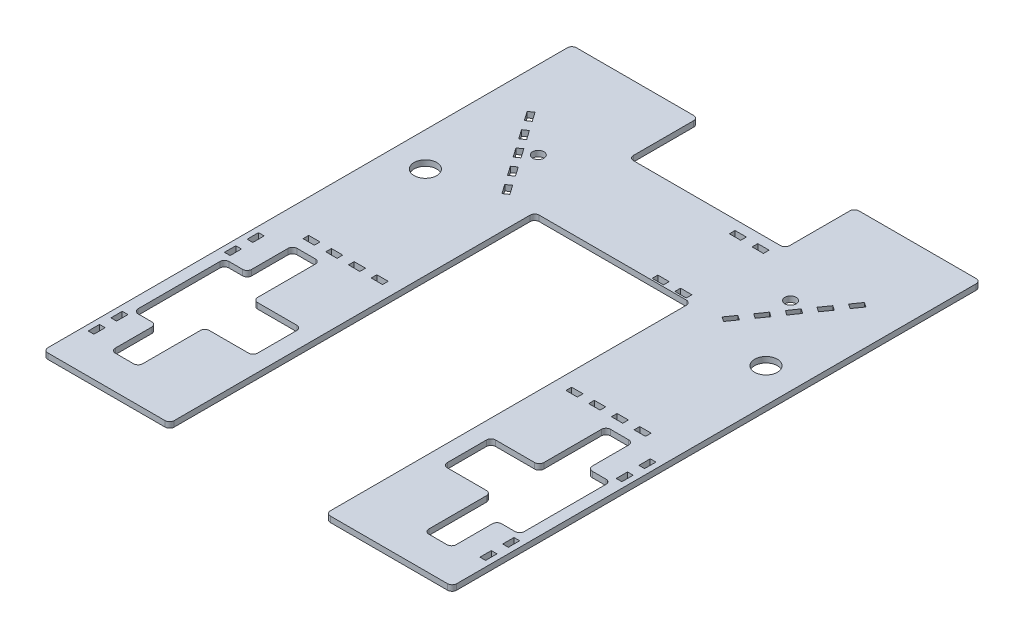
SolidWorks part; units mm, degrees
material "Acrylic (Medium-high impact)"
ref_plane "Front Plane" through (0, 0, 0) normal (0, 0, 1) x (1, 0, 0)
ref_plane "Top Plane" through (0, 0, 0) normal (0, 1, 0) x (1, 0, 0)
ref_plane "Right Plane" through (0, 0, 0) normal (1, 0, 0) x (0, 0, -1)
sketch "Sketch1" plane through (0, 0, 0) normal (0, 1, 0) x (1, 0, 0)
  line L0 (0, 0) -> (0, 279.4)
  line L1 (0, 0) -> (70.625, 0) construction
  line L2 (228.6, 0) -> (228.6, 279.4)
  line L3 (228.6, 279.4) -> (157.975, 178.425) construction
  line L4 (157.975, 178.425) -> (157.975, 0)
  line L5 (194.31, 66.84) -> (167.3225, 66.84)
  line L6 (70.625, 0) -> (70.625, 178.425)
  line L7 (70.625, 178.425) -> (0, 279.4) construction
  line L8 (70.625, 178.425) -> (0, 178.425) construction
  line L9 (157.975, 178.425) -> (228.6, 178.425) construction
  line L10 (0, 279.4) -> (70.625, 279.4)
  line L11 (114.3, -1000) -> (114.3, 49000) construction
  line L12 (194.31, 2.54) -> (209.55, 2.54)
  line L13 (194.31, 2.54) -> (194.31, 39.84)
  line L14 (194.31, 104.14) -> (209.55, 104.14)
  line L15 (222.25, 27.94) -> (222.25, 78.74)
  line L16 (167.3225, 66.84) -> (167.3225, 39.84)
  line L17 (167.3225, 39.84) -> (194.31, 39.84)
  line L18 (194.31, 66.84) -> (194.31, 104.14)
  line L19 (19.05, 78.74) -> (6.35, 78.74)
  line L20 (70.625, 279.4) -> (70.625, 240.6391)
  line L21 (70.625, 240.6391) -> (157.975, 240.6391)
  line L22 (157.975, 240.6391) -> (157.975, 279.4)
  line L23 (157.975, 279.4) -> (228.6, 279.4)
  line L24 (70.625, 178.425) -> (157.975, 178.425) construction
  line L25 (19.05, 27.94) -> (6.35, 27.94)
  line L26 (157.975, 0) -> (228.6, 0) construction
  line L27 (39.37, 53.34) -> (6.35, 53.34) construction
  line L28 (6.35, 27.94) -> (6.35, 78.74)
  line L29 (6.35, 81.915) -> (3.175, 81.915)
  line L30 (6.35, 81.915) -> (6.35, 88.265)
  line L31 (6.35, 88.265) -> (3.175, 88.265)
  line L32 (3.175, 81.915) -> (3.175, 88.265)
  line L33 (6.35, 94.615) -> (3.175, 94.615)
  line L34 (6.35, 94.615) -> (6.35, 100.965)
  line L35 (6.35, 100.965) -> (3.175, 100.965)
  line L36 (3.175, 12.065) -> (3.175, 5.715)
  line L37 (6.35, 5.715) -> (3.175, 5.715)
  line L38 (6.35, 12.065) -> (6.35, 5.715)
  line L39 (6.35, 12.065) -> (3.175, 12.065)
  line L40 (3.175, 24.765) -> (3.175, 18.415)
  line L41 (6.35, 18.415) -> (3.175, 18.415)
  line L42 (6.35, 24.765) -> (6.35, 18.415)
  line L43 (6.35, 24.765) -> (3.175, 24.765)
  line L44 (3.175, 94.615) -> (3.175, 100.965)
  line L45 (19.05, 104.14) -> (19.05, 78.74)
  line L46 (19.05, 2.54) -> (19.05, 27.94)
  line L47 (34.29, 104.14) -> (19.05, 104.14)
  line L48 (34.29, 2.54) -> (34.29, 39.84)
  line L49 (34.29, 2.54) -> (19.05, 2.54)
  line L50 (61.2775, 39.84) -> (34.29, 39.84)
  line L51 (61.2775, 66.84) -> (61.2775, 39.84)
  line L52 (34.29, 66.84) -> (61.2775, 66.84)
  line L53 (34.29, 66.84) -> (34.29, 104.14)
  line L54 (43.955, 113.665) -> (50.305, 113.665)
  line L55 (56.655, 110.49) -> (63.005, 110.49)
  line L56 (56.655, 110.49) -> (56.655, 113.665)
  line L57 (56.655, 113.665) -> (63.005, 113.665)
  line L58 (63.005, 110.49) -> (63.005, 113.665)
  line L59 (43.955, 110.49) -> (43.955, 113.665)
  line L60 (43.955, 110.49) -> (50.305, 110.49)
  line L61 (50.305, 110.49) -> (50.305, 113.665)
  line L62 (31.255, 113.665) -> (37.605, 113.665)
  line L63 (31.255, 110.49) -> (31.255, 113.665)
  line L64 (31.255, 110.49) -> (37.605, 110.49)
  line L65 (37.605, 110.49) -> (37.605, 113.665)
  line L66 (18.555, 113.665) -> (24.905, 113.665)
  line L67 (18.555, 110.49) -> (18.555, 113.665)
  line L68 (18.555, 110.49) -> (24.905, 110.49)
  line L69 (24.905, 110.49) -> (24.905, 113.665)
  line L70 (135.3875, 235.2498) -> (141.7375, 235.2498)
  line L71 (135.3875, 192.0748) -> (141.7375, 192.0748)
  line L72 (135.3875, 192.0748) -> (135.3875, 188.8998)
  line L73 (135.3875, 188.8998) -> (141.7375, 188.8998)
  line L74 (141.7375, 192.0748) -> (141.7375, 188.8998)
  line L75 (148.0875, 192.0748) -> (154.4375, 192.0748)
  line L76 (148.0875, 192.0748) -> (148.0875, 188.8998)
  line L77 (148.0875, 188.8998) -> (154.4375, 188.8998)
  line L78 (203.695, 110.49) -> (203.695, 113.665)
  line L79 (210.045, 110.49) -> (203.695, 110.49)
  line L80 (210.045, 110.49) -> (210.045, 113.665)
  line L81 (210.045, 113.665) -> (203.695, 113.665)
  line L82 (190.995, 110.49) -> (190.995, 113.665)
  line L83 (197.345, 110.49) -> (190.995, 110.49)
  line L84 (197.345, 110.49) -> (197.345, 113.665)
  line L85 (197.345, 113.665) -> (190.995, 113.665)
  line L86 (178.295, 110.49) -> (178.295, 113.665)
  line L87 (184.645, 110.49) -> (178.295, 110.49)
  line L88 (184.645, 110.49) -> (184.645, 113.665)
  line L89 (165.595, 110.49) -> (165.595, 113.665)
  line L90 (171.945, 113.665) -> (165.595, 113.665)
  line L91 (171.945, 110.49) -> (171.945, 113.665)
  line L92 (171.945, 110.49) -> (165.595, 110.49)
  line L93 (184.645, 113.665) -> (178.295, 113.665)
  line L94 (154.4375, 192.0748) -> (154.4375, 188.8998)
  line L95 (135.3875, 235.2498) -> (135.3875, 232.0748)
  line L96 (135.3875, 232.0748) -> (141.7375, 232.0748)
  line L97 (141.7375, 235.2498) -> (141.7375, 232.0748)
  line L98 (148.0875, 235.2498) -> (154.4375, 235.2498)
  line L99 (148.0875, 235.2498) -> (148.0875, 232.0748)
  line L100 (148.0875, 232.0748) -> (154.4375, 232.0748)
  line L101 (154.4375, 235.2498) -> (154.4375, 232.0748)
  line L102 (157.975, 178.425) -> (157.975, 187.95)
  line L103 (157.975, 187.95) -> (70.625, 187.95)
  line L104 (70.625, 187.95) -> (70.625, 178.425)
  line L105 (0, 0) -> (0, -16.1925)
  line L106 (0, -16.1925) -> (70.625, -16.1925)
  line L107 (228.6, -16.1925) -> (228.6, 0)
  line L108 (70.625, 0) -> (70.625, -16.1925)
  line L109 (157.975, 0) -> (157.975, -16.1925)
  line L110 (157.975, -16.1925) -> (228.6, -16.1925)
  line L124 (189.23, 53.34) -> (222.25, 53.34) construction
  line L125 (209.55, 2.54) -> (209.55, 27.94)
  line L126 (209.55, 27.94) -> (222.25, 27.94)
  line L127 (209.55, 78.74) -> (222.25, 78.74)
  line L128 (209.55, 104.14) -> (209.55, 78.74)
  line L134 (225.425, 94.615) -> (225.425, 100.965)
  line L135 (222.25, 24.765) -> (225.425, 24.765)
  line L136 (222.25, 24.765) -> (222.25, 18.415)
  line L137 (222.25, 18.415) -> (225.425, 18.415)
  line L138 (225.425, 24.765) -> (225.425, 18.415)
  line L139 (222.25, 12.065) -> (225.425, 12.065)
  line L140 (222.25, 12.065) -> (222.25, 5.715)
  line L141 (222.25, 5.715) -> (225.425, 5.715)
  line L142 (225.425, 12.065) -> (225.425, 5.715)
  line L143 (222.25, 100.965) -> (225.425, 100.965)
  line L144 (222.25, 94.615) -> (222.25, 100.965)
  line L145 (222.25, 94.615) -> (225.425, 94.615)
  line L146 (225.425, 81.915) -> (225.425, 88.265)
  line L147 (222.25, 88.265) -> (225.425, 88.265)
  line L148 (222.25, 81.915) -> (222.25, 88.265)
  line L149 (222.25, 81.915) -> (225.425, 81.915)
  line L166 (173.659, 189.7697) -> (177.2985, 194.9733)
  line L167 (173.659, 189.7697) -> (176.2607, 187.95)
  line L168 (178.9875, 197.6665) -> (181.5892, 195.8467) construction
  line L169 (176.2607, 187.95) -> (179.9002, 193.1535)
  line L170 (177.2985, 194.9733) -> (179.9002, 193.1535)
  line L171 (180.9379, 200.1768) -> (183.5397, 198.357)
  line L172 (187.1792, 203.5605) -> (183.5397, 198.357)
  line L173 (184.5774, 205.3803) -> (187.1792, 203.5605)
  line L174 (184.5774, 205.3803) -> (180.9379, 200.1768)
  line L175 (182.627, 202.87) -> (185.2287, 201.0502) construction
  line L176 (186.2665, 208.0735) -> (188.8682, 206.2537) construction
  line L177 (29.4646, 226.1943) -> (33.1041, 220.9908)
  line L178 (188.2169, 210.5838) -> (191.8564, 215.7873)
  line L179 (188.2169, 210.5838) -> (190.8187, 208.7641)
  line L180 (190.8187, 208.7641) -> (194.4582, 213.9676)
  line L181 (191.8564, 215.7873) -> (194.4582, 213.9676)
  line L182 (195.4959, 220.9908) -> (198.0977, 219.1711)
  line L183 (201.7372, 224.3746) -> (198.0977, 219.1711)
  line L184 (199.1354, 226.1943) -> (201.7372, 224.3746)
  line L185 (199.1354, 226.1943) -> (195.4959, 220.9908)
  line L186 (29.4646, 226.1943) -> (26.8628, 224.3746)
  line L187 (26.8628, 224.3746) -> (30.5023, 219.1711)
  line L188 (33.1041, 220.9908) -> (30.5023, 219.1711)
  line L189 (36.7436, 215.7873) -> (34.1418, 213.9676)
  line L190 (37.7813, 208.7641) -> (34.1418, 213.9676)
  line L191 (40.3831, 210.5838) -> (37.7813, 208.7641)
  line L192 (40.3831, 210.5838) -> (36.7436, 215.7873)
  line L193 (47.6621, 200.1768) -> (45.0603, 198.357)
  line L194 (44.0226, 205.3803) -> (47.6621, 200.1768)
  line L195 (44.0226, 205.3803) -> (41.4208, 203.5605)
  line L196 (41.4208, 203.5605) -> (45.0603, 198.357)
  line L197 (51.3015, 194.9733) -> (48.6998, 193.1535)
  line L198 (52.3393, 187.95) -> (48.6998, 193.1535)
  line L199 (54.941, 189.7697) -> (52.3393, 187.95)
  line L200 (54.941, 189.7697) -> (51.3015, 194.9733)
  line L201 (197.1849, 223.684) -> (199.7867, 221.8643) construction
  line L202 (202.7749, 231.3979) -> (205.3767, 229.5781)
  line L203 (209.0162, 234.7816) -> (205.3767, 229.5781)
  line L204 (206.4144, 236.6014) -> (202.7749, 231.3979)
  line L205 (206.4144, 236.6014) -> (209.0162, 234.7816)
  line L206 (22.1856, 236.6014) -> (19.5838, 234.7816)
  line L207 (22.1856, 236.6014) -> (25.8251, 231.3979)
  line L208 (19.5838, 234.7816) -> (23.2233, 229.5781)
  line L209 (25.8251, 231.3979) -> (23.2233, 229.5781)
  line L210 (5.855, 113.665) -> (12.205, 113.665) [skipped]
  line L211 (5.855, 110.49) -> (5.855, 113.665) [skipped]
  line L212 (5.855, 110.49) -> (12.205, 110.49) [skipped]
  line L213 (12.205, 110.49) -> (12.205, 113.665) [skipped]
  circle A0 centre (184.8332, 216.8251) radius 3.175
  circle A1 centre (209.55, 178.425) radius 6.35
  circle A2 centre (43.7668, 216.8251) radius 3.175
  circle A3 centre (19.05, 178.425) radius 6.35
  dimension "D27" = 0
  dimension "D26" = 12.7
  dimension "D29" = 9.525
  dimension "D41" = 16.1925
  dimension "D15" = 6.35
  dimension "D1" = 279.4
  dimension "D3" = 87.35
  dimension "D5" = 228.6
  dimension "D6" = 101.6
  dimension "D7" = 27.94
  dimension "D8" = 6.35
  dimension "D9" = 38.7609
  dimension "D10" = 114.3
  dimension "D11" = 100.975
  dimension "D12" = 27
  dimension "D13" = 13.5
  dimension "D14" = 26.9875
  dimension "D16" = 6.35
  dimension "D17" = 7.62
  dimension "D18" = 5
  dimension "D19" = 6.35
  dimension "D20" = 13.6498
  dimension "D21" = 93.2125
  dimension "D22" = 6.35
  dimension "D23" = 40
  dimension "D24" = 46.8607
  dimension "D25" = 2.54
  dimension "D28" = 19.05
  dimension "D30" = 25.4
  dimension "D31" = 12.7
  dimension "D32" = 6.35
  dimension "D33" = 3.175
  dimension "D34" = 3.175
  dimension "D35" = 6.35
  dimension "D36" = 6.35
  dimension "D37" = 9.525
  dimension "D38" = 3.175
  dimension "D39" = 6.35
  dimension "D40" = 3.175
extrude "Boss-Extrude1" add sketch "Sketch1" along normal blind 3.175
fillet "Fillet1" radius 2.54 36 edges at (157.975, 1.5875, -279.4) (70.625, 1.5875, -279.4) (157.975, 1.5875, -240.6391) (70.625, 1.5875, -240.6391) (157.975, 1.5875, -187.95) (70.625, 1.5875, -187.95) (228.6, 1.5875, -279.4) (0, 1.5875, -279.4) (34.29, 1.5875, -2.54) (19.05, 1.5875, -2.54) (19.05, 1.5875, -27.94) (6.35, 1.5875, -27.94) (6.35, 1.5875, -78.74) (19.05, 1.5875, -78.74) (19.05, 1.5875, -104.14) (34.29, 1.5875, -104.14) (34.29, 1.5875, -39.84) (34.29, 1.5875, -66.84) (61.2775, 1.5875, -39.84) (61.2775, 1.5875, -66.84) (167.3225, 1.5875, -39.84) (194.31, 1.5875, -39.84) (194.31, 1.5875, -2.54) (209.55, 1.5875, -2.54) (209.55, 1.5875, -27.94) (222.25, 1.5875, -27.94) (222.25, 1.5875, -78.74) (209.55, 1.5875, -78.74) (209.55, 1.5875, -104.14) (194.31, 1.5875, -104.14) (194.31, 1.5875, -66.84) (167.3225, 1.5875, -66.84) (157.975, 1.5875, 16.1925) (70.625, 1.5875, 16.1925) (228.6, 1.5875, 16.1925) (0, 1.5875, 16.1925)
